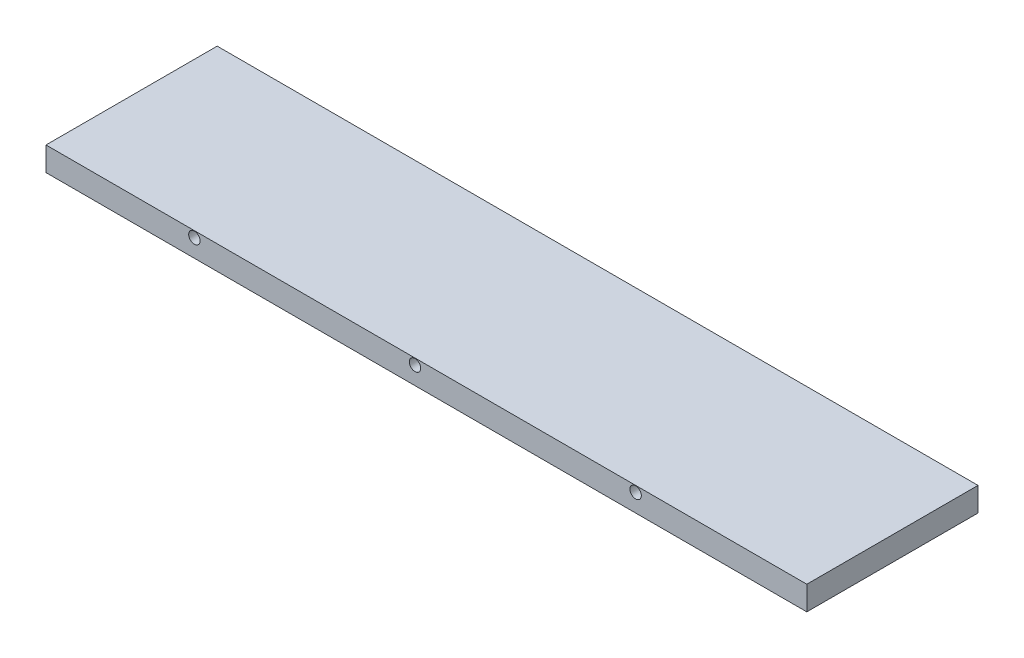
SolidWorks part; units mm, degrees
ref_plane "Front Plane" through (0, 0, 0) normal (0, 0, 1) x (1, 0, 0)
ref_plane "Top Plane" through (0, 0, 0) normal (0, 1, 0) x (1, 0, 0)
ref_plane "Right Plane" through (0, 0, 0) normal (1, 0, 0) x (0, 0, -1)
sketch "Sketch1" plane through (0, 0, 0) normal (0, 1, 0) x (1, 0, 0)
  line L1 (-34.0308, 14.4884) -> (219.9692, 14.4884)
  line L2 (-34.0308, 14.4884) -> (-34.0308, -42.6616)
  line L3 (-34.0308, -42.6616) -> (219.9692, -42.6616)
  line L4 (219.9692, 14.4884) -> (219.9692, -42.6616)
  circle A3 centre (202.9692, 0.5184) radius 10
  circle A4 centre (171.2192, 0.5184) radius 10
  circle A5 centre (139.4692, 0.5184) radius 10
  circle A6 centre (107.7192, 0.5184) radius 10
  circle A7 centre (75.9692, 0.5184) radius 10
  circle A8 centre (44.2192, 0.5184) radius 10
  circle A10 centre (171.2192, -22.3416) radius 10
  circle A11 centre (139.4692, -22.3416) radius 10
  circle A12 centre (107.7192, -22.3416) radius 10
  circle A13 centre (75.9692, -22.3416) radius 10
  circle A14 centre (44.2192, -22.3416) radius 10
  circle A16 centre (202.9692, -22.3416) radius 10
  circle A17 centre (12.4692, 0.5184) radius 10
  circle A18 centre (-19.2808, 0.5184) radius 10
  circle A19 centre (12.4692, -22.3416) radius 10
  circle A20 centre (-19.2808, -22.3416) radius 10
  dimension "D3" = 8
  dimension "D5" = 13.97
  dimension "D7" = 22.86
  dimension "D9" = 20
  dimension "D1" = 254
  dimension "D2" = 57.15
  dimension "D4" = 2
  dimension "D6" = 31.75
  dimension "D10" = 17
extrude "Boss-Extrude1" add sketch "Sketch1" along normal blind 8
sketch "Sketch25" plane through (0, 0, 0) normal (0, -1, 0) x (1, 0, 0)
  line L0 (-34.0308, -14.4884) -> (-34.0308, 42.6616) construction
  circle A0 centre (44.2192, 22.3416) radius 10.25
  circle A1 centre (75.9692, 22.3416) radius 10.25
  circle A2 centre (107.7192, 22.3416) radius 10.25
  circle A3 centre (139.4692, 22.3416) radius 10.25
  circle A4 centre (171.2192, 22.3416) radius 10.25
  circle A5 centre (202.9692, 22.3416) radius 10.25
  circle A6 centre (75.9692, -0.5184) radius 10.25
  circle A7 centre (107.7192, -0.5184) radius 10.25
  circle A8 centre (139.4692, -0.5184) radius 10.25
  circle A9 centre (171.2192, -0.5184) radius 10.25
  circle A10 centre (202.9692, -0.5184) radius 10.25
  circle A11 centre (44.2192, -0.5184) radius 10.25
  circle A16 centre (12.4692, 22.3416) radius 10.25
  circle A17 centre (-19.2808, 22.3416) radius 10.25
  circle A18 centre (-19.2808, -0.5184) radius 10.25
  circle A19 centre (12.4692, -0.5184) radius 10.25
  dimension "D1" = 20.5
  dimension "D7" = 20.5
  dimension "D4" = 78.25
  dimension "D5" = 22.86
  dimension "D6" = 31.75
  dimension "D2" = 6
  dimension "D3" = 2
  dimension "D8" = 2
  dimension "D9" = 2
extrude "Cut-Extrude1" cut sketch "Sketch25" against normal blind 7.6
sketch "Sketch3" plane through (0, 0, -14.4884) normal (0, 0, -1) x (-1, 0, 0)
  line L0 (-219.9692, 8) -> (34.0308, 8) construction
  line L3 (34.0308, 8) -> (34.0308, 0) construction
  point P0 (-148.8492, 4.19)
  point P6 (-21.8492, 4.19)
  point P7 (-21.8492, 4.19)
  point P8 (-85.3492, 4.19)
  dimension "D1" = 3.81
  dimension "D2" = 63.5
  dimension "D4" = 63.5
  dimension "D5" = 55.88
  dimension "D3" = 3
sketch "Sketch26" plane through (0, 8, 0) normal (0, 1, 0) x (1, 0, 0)
  line L1 (-34.0308, 14.4884) -> (219.9692, 14.4884)
  line L2 (-34.0308, 14.4884) -> (-34.0308, -42.6616)
  line L3 (-34.0308, -42.6616) -> (219.9692, -42.6616)
  line L4 (219.9692, 14.4884) -> (219.9692, -42.6616)
extrude "Boss-Extrude2" add sketch "Sketch26" against normal blind 0.4
sketch "Sketch4" plane through (0, 0, 42.6616) normal (0, 0, 1) x (1, 0, 0)
  line L1 (-34.0308, 8) -> (219.9692, 8) construction
  line L2 (-34.0308, 8) -> (-34.0308, 0) construction
  point P5 (15.4992, 5.968)
  point P6 (162.8192, 5.968)
  point P8 (82.8092, 2.032)
  point P12 (89.1592, 5.968)
  dimension "D1" = 2.032
  dimension "D2" = 49.53
  dimension "D3" = 73.66
  dimension "D4" = 73.66
hole_wizard "#25 (0.1495) Diameter Hole2" positions "Sketch15" profile "Sketch16" hole size "#25" standard "ANSI Inch"
sketch "Sketch15" plane through (0, 0, 42.6616) normal (0, 0, 1) x (1, 0, 0)
  point P0 (15.4992, 5.968)
  point P9 (162.8192, 5.968)
  point P12 (89.1592, 5.968)
sketch "Sketch16" plane through (15.4992, 5.968, 42.6616) normal (1, 0, 0) x (0, -1, 0)
  line L0 (0, 0) -> (0, 7.4908)
  line L1 (0, 7.4908) -> (1.8986, 6.35)
  line L2 (1.8986, 6.35) -> (1.8986, 0)
  line L5 (1.8986, 0) -> (0, 0)
  line L10 (0, 7.4908) -> (-1.8987, 6.35) construction
  line L11 (0, -6.35) -> (0, 107.95) construction
  dimension "Hole Dia." = 3.7973
  dimension "Hole Depth" = 6.35
  dimension "Drill Angle" = 118
hole_wizard "#25 (0.1495) Diameter Hole1" positions "Sketch23" profile "Sketch24" hole size "#25" standard "ANSI Inch"
sketch "Sketch23" plane through (0, 0, -14.4884) normal (0, 0, -1) x (-1, 0, 0)
  point P0 (-148.8492, 4.19)
  point P3 (-85.3492, 4.19)
  point P15 (-21.8492, 4.19)
sketch "Sketch24" plane through (148.8492, 4.19, -14.4884) normal (1, 0, 0) x (0, 1, 0)
  line L0 (0, 0) -> (0, 7.4908)
  line L1 (0, 7.4908) -> (1.8986, 6.35)
  line L2 (1.8986, 6.35) -> (1.8986, 0)
  line L5 (1.8986, 0) -> (0, 0)
  line L10 (0, 7.4908) -> (-1.8987, 6.35) construction
  line L11 (0, -6.35) -> (0, 107.95) construction
  dimension "Hole Dia." = 3.7973
  dimension "Hole Depth" = 6.35
  dimension "Drill Angle" = 118
